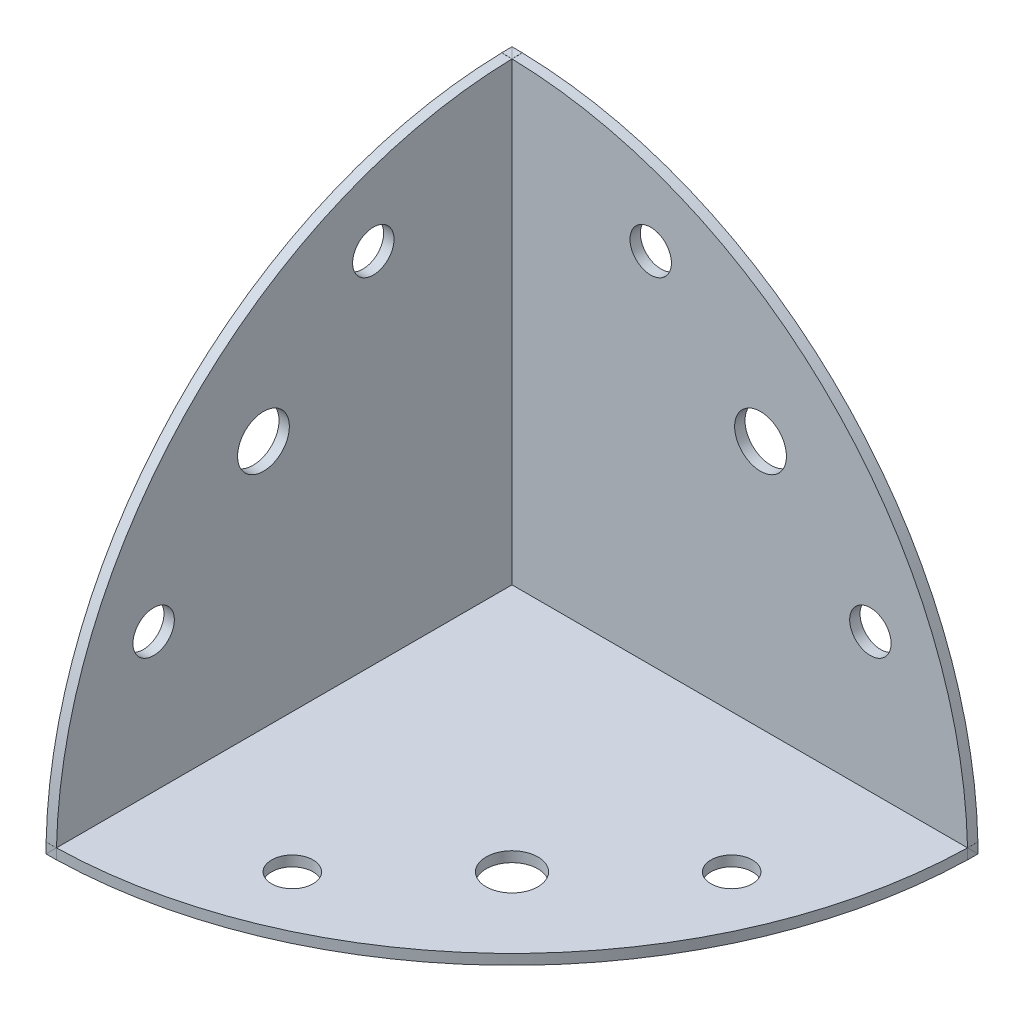
SolidWorks part; units mm, degrees
material "AISI 316 Отожженная нержавеющая сталь. полоса (SS)"
ref_plane "Спереди (XY)" through (0, 0, 0) normal (0, 0, 1) x (1, 0, 0)
ref_plane "Сверху (XZ)" through (0, 0, 0) normal (0, 1, 0) x (1, 0, 0)
ref_plane "Справа (ZY)" through (0, 0, 0) normal (1, 0, 0) x (0, 0, -1)
sketch "Эскиз2" plane through (0, 0, 0) normal (0, 1, 0) x (1, 0, 0)
  line L0 (0, 45.738) -> (0, -60.0775) construction
  line L1 (-46.4797, 0) -> (54.3912, 0) construction
  line L2 (0, -45) -> (0, 0)
  line L3 (0, 0) -> (45, 0)
  line L4 (0, 0) -> (25.6564, -25.6564) construction
  line L5 (25, -25) -> (3.4441, -25) construction
  line L6 (25, -25) -> (25, -7.0659) construction
  line L7 (9.0873, -40.9127) -> (25, -25) construction
  arc A0 (45, 0) -> (0, -45) centre (0, 0) cw
  circle A1 centre (25, -25) radius 2.5
  circle A2 centre (14.3934, -35.6066) radius 2
  circle A3 centre (35.6066, -14.3934) radius 2
  point P14 (14.2221, -25)
  dimension "D1" = 45
  dimension "D3" = 5
  dimension "D5" = 7.6212
  dimension "D7" = 4
  dimension "D2" = 45
  dimension "D4" = 25
  dimension "D6" = 45
  dimension "D8" = 15
extrude "Бобышка-Вытянуть1" add sketch "Эскиз2" along normal blind 1
sketch "Эскиз3" plane through (0, 0, 0) normal (0, 0, 1) x (1, 0, 0)
  line L0 (0, 39.8582) -> (0, -33.4649) construction
  line L1 (45, 0) -> (0, 0) construction
  line L2 (0, 45) -> (0, 0)
  line L3 (0, 0) -> (45, 0)
  line L4 (0, 0) -> (27.1358, 27.1358) construction
  line L5 (25, 25) -> (8.5216, 41.4784) construction
  arc A0 (0, 45) -> (45, 0) centre (0, 0) cw
  circle A1 centre (25, 25) radius 2.5
  circle A2 centre (14.3934, 35.6066) radius 2
  circle A3 centre (35.6066, 14.3934) radius 2
  dimension "D1" = 45
  dimension "D4" = 5
  dimension "D5" = 4
  dimension "D2" = 45
  dimension "D3" = 25
  dimension "D6" = 15
extrude "Бобышка-Вытянуть2" add sketch "Эскиз3" along normal blind 1
sketch "Эскиз5" plane through (0, 0, 0) normal (1, 0, 0) x (0, 0, -1)
  line L0 (0, 45) -> (0, 0) construction
  line L1 (0, 0) -> (-45, 0) construction
  line L2 (0, 45) -> (0, 0)
  line L3 (0, 0) -> (-45, 0)
  line L4 (0, 0) -> (-27.4252, 27.4252) construction
  line L5 (-25, 25) -> (-10.7619, 39.2381) construction
  arc A0 (0, 45) -> (-45, 0) centre (0, 0) ccw
  circle A1 centre (-25, 25) radius 2.5
  circle A2 centre (-14.3934, 35.6066) radius 2
  circle A3 centre (-35.6066, 14.3934) radius 2
  dimension "D1" = 45
  dimension "D3" = 5
  dimension "D5" = 4
  dimension "D2" = 45
  dimension "D4" = 25
  dimension "D6" = 15
extrude "Бобышка-Вытянуть3" add sketch "Эскиз5" along normal blind 1
